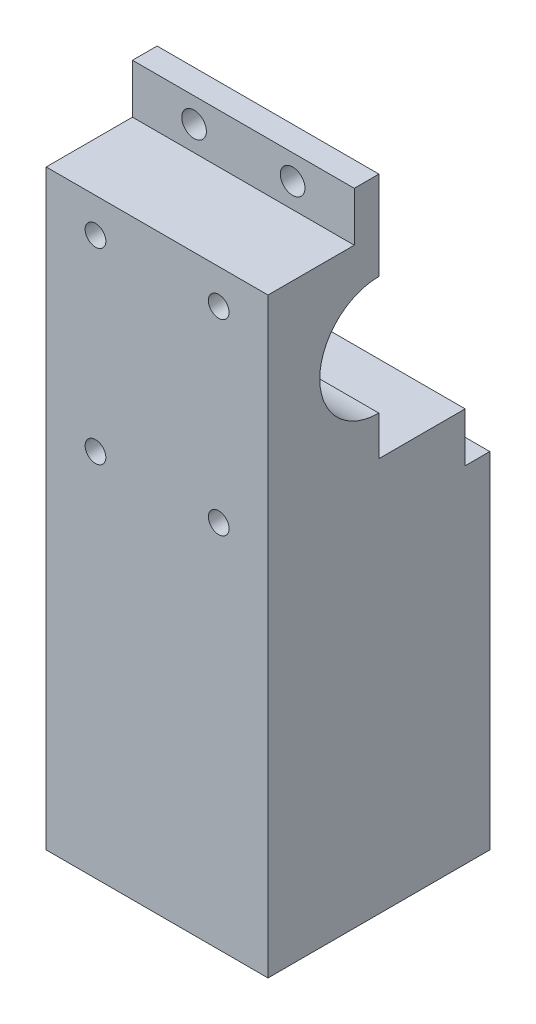
SolidWorks part; units mm, degrees
material "不锈钢 (铁素体)"
ref_plane "前视" through (0, 0, 0) normal (0, 0, 1) x (1, 0, 0)
ref_plane "上视" through (0, 0, 0) normal (0, 1, 0) x (1, 0, 0)
ref_plane "右视" through (0, 0, 0) normal (1, 0, 0) x (0, 0, -1)
sketch "草图1" plane through (0, 0, 0) normal (0, 1, 0) x (1, 0, 0)
  line L1 (-22.5, -22.5) -> (22.5, -22.5)
  line L2 (-22.5, -22.5) -> (-22.5, 22.5)
  line L3 (-22.5, 22.5) -> (22.5, 22.5)
  line L4 (22.5, -22.5) -> (22.5, 22.5)
  line L5 (-22.5, -22.5) -> (22.5, 22.5) construction
  line L6 (-22.5, 22.5) -> (22.5, -22.5) construction
  point P0 (0, 0)
  dimension "D1" = 45
  dimension "D2" = 45
extrude "凸台-拉伸1" add sketch "草图1" along normal blind 80
hole_wizard "M36 螺纹孔1" positions "草图2" profile "草图4" tap size "M36" standard "GB"
sketch "草图2" plane through (0, 0, 0) normal (0, -1, 0) x (-1, 0, 0)
  point P0 (0, 0)
sketch "草图4" plane through (0, 0, 0) normal (1, 0, 0) x (0, 0, -1)
  line L0 (0, 0) -> (0, 59.6138)
  line L1 (0, 59.6138) -> (16, 50)
  line L2 (16, 50) -> (16, 3)
  line L3 (16, 3) -> (19, 0)
  line L5 (19, 0) -> (0, 0)
  line L6 (-16, 3) -> (-19, 0) construction
  line L10 (0, 59.6138) -> (-16, 50) construction
  line L11 (0, -6.35) -> (0, 107.95) construction
  dimension "螺纹孔钻头直径" = 32
  dimension "螺纹孔钻头深度" = 50
  dimension "近端锥形沉头孔直径" = 38
  dimension "近端锥形沉头孔角度" = 90
  dimension "导头角度" = 118
cosmetic thread "孔螺蚊线1" parameters "D1"=50, "D2"=36
sketch "草图6" plane through (22.5, 0, 0) normal (1, 0, 0) x (0, 0, -1)
  line L0 (-22.5, 80) -> (-22.5, 120)
  line L1 (-22.5, 120) -> (0, 120)
  line L2 (0, 120) -> (0, 112)
  line L3 (0, 88) -> (0, 80)
  line L4 (-22.5, 80) -> (22.5, 80) construction
  line L5 (-22.5, 100) -> (6.5979, 100) construction
  line L6 (-22.5, 80) -> (0, 80)
  line L7 (-5, 120) -> (-5, 130)
  line L8 (-5, 130) -> (0, 130)
  line L9 (0, 130) -> (0, 120)
  line L10 (-22.5, 0) -> (22.5, 0)
  line L11 (22.5, 0) -> (22.5, 80)
  line L12 (22.5, 80) -> (-22.5, 80)
  line L13 (-22.5, 80) -> (-22.5, 0)
  line L14 (-22.5, 0) -> (22.5, 0)
  line L15 (22.5, 0) -> (22.5, 80)
  line L16 (22.5, 80) -> (0, 80)
  line L17 (-22.5, 80) -> (-22.5, 0)
  arc A0 (0, 112) -> (0, 88) centre (0, 100) ccw
  line M9 (22.5, 80) -> (-22.5, 80)
  dimension "D1" = 12
  dimension "D2" = 40
  dimension "D4" = 5
  dimension "D5" = 10
  dimension "D3" = 0
extrude "凸台-拉伸2" add sketch "草图6" against normal up to surface (45 mm away) contours L5 L0 L3 A0 M9 | L0 L5 A0 L2 L1 | L9 L8 L7 L1 up to face at (-22.5, 40, 0)
sketch "草图7" plane through (0, 0, 5) normal (0, 0, 1) x (1, 0, 0)
  line L0 (0, 138.9603) -> (0, 100.3762) construction
  line L1 (-22.5, 130) -> (22.5, 130) construction
  circle A0 centre (10, 125) radius 2.5
  circle A1 centre (-10, 125) radius 2.5
  dimension "D1" = 5
  dimension "D2" = 20
  dimension "D3" = 5
  dimension "D4" = 20
extrude "切除-拉伸1" cut sketch "草图7" against normal through all
sketch "草图8" plane through (22.5, 0, 0) normal (1, 0, 0) x (0, 0, -1)
  line L1 (22.5, 80) -> (17.5, 80)
  line L2 (22.5, 80) -> (22.5, 70)
  line L3 (22.5, 70) -> (17.5, 70)
  line L4 (17.5, 80) -> (17.5, 70)
  dimension "D1" = 10
  dimension "D2" = 5
extrude "切除-拉伸2" cut sketch "草图8" against normal through all
sketch "草图9" plane through (0, 0, -17.5) normal (0, 0, -1) x (-1, 0, 0)
  line L0 (-22.5, 80) -> (-22.5, 70) construction
  line L1 (22.5, 80) -> (22.5, 70) construction
  line L2 (22.5, 80) -> (-22.5, 80) construction
  circle A0 centre (-12.5, 75) radius 2.5
  circle A1 centre (12.5, 75) radius 2.5
  circle A2 centre (-10, 125) radius 2.5 construction
  dimension "D1" = 10
  dimension "D2" = 10
  dimension "D3" = 5
sketch "草图10" plane through (0, 0, 22.5) normal (0, 0, 1) x (1, 0, 0)
  line L0 (-22.5, 0) -> (22.5, 0) construction
  line L1 (0, 0) -> (0, 96.3767) construction
  circle A0 centre (-12.5, 75) radius 2.5
  circle A1 centre (12.5, 75) radius 2.5
  circle A2 centre (-12.5, 113) radius 2.5
  circle A3 centre (12.5, 113) radius 2.5
  point P2 (0, 0)
  dimension "D1" = 5
  dimension "D2" = 5
  dimension "D6" = 5
  dimension "D3" = 75
  dimension "D4" = 12.5
  dimension "D5" = 38
hole_wizard "M5 螺纹孔的螺纹孔钻头1" positions "3D草图1" profile "草图11" hole size "M5" standard "GB"
sketch3d "3D草图1"
  point P0 (-12.5, 75, 22.5)
  point P3 (12.5, 75, 22.5)
sketch "草图11" plane through (-12.5, 75, 22.5) normal (1, 0, 0) x (0, -1, 0)
  line L0 (0, 0) -> (0, 16.2618)
  line L1 (0, 16.2618) -> (2.1, 15)
  line L2 (2.1, 15) -> (2.1, 0)
  line L5 (2.1, 0) -> (0, 0)
  line L10 (0, 16.2618) -> (-2.1, 15) construction
  line L11 (0, -6.35) -> (0, 107.95) construction
  dimension "孔直径" = 4.2
  dimension "孔深度" = 15
  dimension "导头角度" = 118
hole_wizard "M5 螺纹孔的螺纹孔钻头2" positions "3D草图2" profile "草图12" hole size "M5" standard "GB"
sketch3d "3D草图2"
  point P0 (12.5, 75, -17.5)
  point P3 (-12.5, 75, -17.5)
  point P7 (-12.5, 113, 22.5)
  point P10 (12.5, 113, 22.5)
sketch "草图12" plane through (12.5, 75, -17.5) normal (1, 0, 0) x (0, 1, 0)
  line L0 (0, 0) -> (0, 11.2618)
  line L1 (0, 11.2618) -> (2.1, 10)
  line L2 (2.1, 10) -> (2.1, 0)
  line L5 (2.1, 0) -> (0, 0)
  line L10 (0, 11.2618) -> (-2.1, 10) construction
  line L11 (0, -6.35) -> (0, 107.95) construction
  dimension "孔直径" = 4.2
  dimension "孔深度" = 10
  dimension "导头角度" = 118
